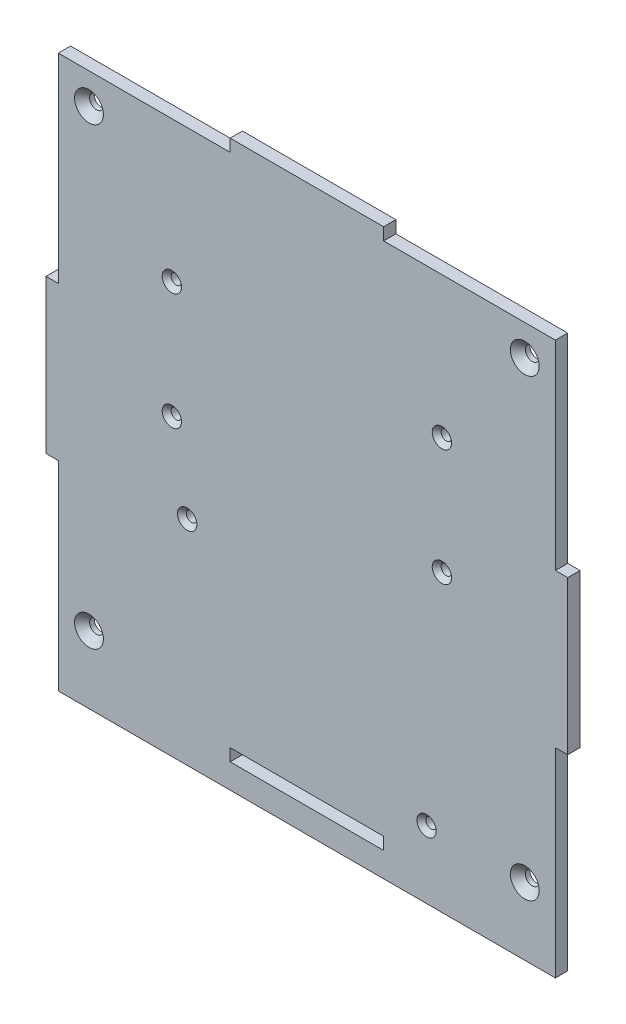
SolidWorks part; units mm, degrees
ref_plane "Front Plane" through (0, 0, 0) normal (0, 0, 1) x (1, 0, 0)
ref_plane "Top Plane" through (0, 0, 0) normal (0, 1, 0) x (1, 0, 0)
ref_plane "Right Plane" through (0, 0, 0) normal (1, 0, 0) x (0, 0, -1)
sketch "Sketch1" plane through (0, 0, 0) normal (0, 0, 1) x (1, 0, 0)
  line L0 (0, 104) -> (0, 10) construction
  line L1 (-81, -80) -> (81, -80)
  line L2 (-81, -80) -> (-81, 100)
  line L3 (-81, 100) -> (81, 100)
  line L4 (81, -80) -> (81, 100)
  line L5 (-81, -80) -> (81, 100) construction
  line L6 (-81, 100) -> (81, -80) construction
  line L7 (-81, 35) -> (-85, 35)
  line L8 (-81, 35) -> (-81, -15)
  line L9 (-81, -15) -> (-85, -15)
  line L10 (-85, 35) -> (-85, -15)
  line L11 (-25, 100) -> (25, 100)
  line L12 (-25, 100) -> (-25, 104)
  line L13 (-25, 104) -> (25, 104)
  line L14 (25, 100) -> (25, 104)
  line L15 (0, 10) -> (-85, 10) construction
  line L24 (81, -15) -> (85, -15)
  line L25 (85, 35) -> (85, -15)
  line L26 (81, 35) -> (85, 35)
  line L27 (81, 35) -> (81, -15)
  line L28 (0, 10) -> (0, 0)
  point P0 (0, 0)
  dimension "D1" = 162
  dimension "D2" = 180
  dimension "D3" = 4
  dimension "D4" = 4
  dimension "D5" = 50
  dimension "D6" = 50
  dimension "D7" = 100
extrude "Boss-Extrude2" add sketch "Sketch1" along normal blind 4
sketch "Sketch2" plane through (0, 0, 4) normal (0, 0, 1) x (1, 0, 0)
  line L0 (0, 0) -> (0, -70)
  line L1 (-25, -72) -> (25, -72)
  line L2 (-25, -72) -> (-25, -68)
  line L3 (-25, -68) -> (25, -68)
  line L4 (25, -72) -> (25, -68)
  line L5 (-25, -72) -> (25, -68) construction
  line L6 (-25, -68) -> (25, -72) construction
  point P0 (0, -70)
  dimension "D1" = 70
  dimension "D2" = 50
  dimension "D3" = 4
extrude "Cut-Extrude1" cut sketch "Sketch2" against normal up to next contours L3 L4 L1 L2
sketch "Sketch3" plane through (0, 0, 4) normal (0, 0, 1) x (1, 0, 0)
  line L0 (0, 35) -> (0, 0)
  line L1 (-44, 16) -> (44, 16)
  line L2 (-44, 16) -> (-44, 54)
  line L3 (-44, 54) -> (44, 54)
  line L4 (44, 16) -> (44, 54)
  line L5 (-44, 16) -> (44, 54) construction
  line L6 (-44, 54) -> (44, 16) construction
  point P0 (0, 35)
  dimension "D1" = 88
  dimension "D2" = 38
  dimension "D3" = 35
hole_wizard "CSK for M3 Countersunk Flat Head Screw1" positions "3DSketch1" profile "Sketch4" countersink size "M3" standard "ISO" end condition up to next
sketch3d "3DSketch1"
  point P0 (-44, 54, 4)
  point P3 (44, 54, 4)
  point P6 (44, 16, 4)
  point P9 (-44, 16, 4)
sketch "Sketch4" plane through (-44, 54, 4) normal (1, 0, 0) x (0, -1, 0)
  line L0 (0, 0) -> (0, 4)
  line L1 (0, 4) -> (1.7, 4)
  line L2 (1.7, 4) -> (1.7, 1.45)
  line L3 (1.7, 1.45) -> (3.15, 0)
  line L5 (3.15, 0) -> (0, 0)
  line L6 (-1.7, 1.45) -> (-3.15, 0) construction
  line L11 (0, -6.35) -> (0, 107.95) construction
  dimension "Thru Hole Dia." = 3.4
  dimension "Thru Hole Depth" = 4
  dimension "Near C'Sink Dia." = 6.3
  dimension "Near C'Sink Angle" = 90
sketch "Sketch5" plane through (0, 0, 4) normal (0, 0, 1) x (1, 0, 0)
  line L0 (-25, -68) -> (25, -68) construction
  line L1 (-71, 90) -> (71, 90)
  line L2 (-71, 90) -> (-71, -58)
  line L3 (-71, -58) -> (71, -58)
  line L4 (71, 90) -> (71, -58)
  line L5 (25, 100) -> (81, 100) construction
  line L6 (81, 35) -> (81, 100) construction
  line L7 (-81, 35) -> (-81, 100) construction
  dimension "D1" = 10
  dimension "D2" = 10
  dimension "D3" = 10
  dimension "D4" = 10
hole_wizard "CSK for M4 Countersunk Flat Head Screw1" positions "3DSketch2" profile "Sketch6" countersink size "M4" standard "ISO" end condition up to next
sketch3d "3DSketch2"
  point P0 (-71, 90, 4)
  point P3 (71, 90, 4)
  point P6 (71, -58, 4)
  point P9 (-71, -58, 4)
sketch "Sketch6" plane through (-71, 90, 4) normal (1, 0, 0) x (0, -1, 0)
  line L0 (0, 0) -> (0, 4)
  line L1 (0, 4) -> (2.25, 4)
  line L2 (2.25, 4) -> (2.25, 2.45)
  line L3 (2.25, 2.45) -> (4.7, 0)
  line L5 (4.7, 0) -> (0, 0)
  line L6 (-2.25, 2.45) -> (-4.7, 0) construction
  line L11 (0, -6.35) -> (0, 107.95) construction
  dimension "Thru Hole Dia." = 4.5
  dimension "Thru Hole Depth" = 4
  dimension "Near C'Sink Dia." = 9.4
  dimension "Near C'Sink Angle" = 90
sketch "Sketch7" plane through (0, 0, 4) normal (0, 0, 1) x (1, 0, 0)
  line L0 (-25, -68) -> (25, -68) construction
  line L5 (-39, -58) -> (39, -58)
  line L6 (-39, -58) -> (-39, -10.5)
  line L7 (-39, -10.5) -> (39, -10.5)
  line L8 (39, -58) -> (39, -10.5)
  line L9 (-39, -58) -> (39, -10.5) construction
  line L10 (-39, -10.5) -> (39, -58) construction
  line L11 (0, 0) -> (0, -34.25)
  point P0 (0, -34.25)
  dimension "D1" = 47.5
  dimension "D2" = 78
  dimension "D3" = 10
hole_wizard "CSK for M3 Countersunk Flat Head Screw3" positions "3DSketch4" profile "Sketch9" countersink size "M3" standard "ISO" end condition up to next
sketch3d "3DSketch4"
  point P0 (-39, -10.5, 4)
  point P3 (39, -58, 4)
sketch "Sketch9" plane through (-39, -10.5, 4) normal (1, 0, 0) x (0, -1, 0)
  line L0 (0, 0) -> (0, 4)
  line L1 (0, 4) -> (1.7, 4)
  line L2 (1.7, 4) -> (1.7, 1.45)
  line L3 (1.7, 1.45) -> (3.15, 0)
  line L5 (3.15, 0) -> (0, 0)
  line L6 (-1.7, 1.45) -> (-3.15, 0) construction
  line L11 (0, -6.35) -> (0, 107.95) construction
  dimension "Thru Hole Dia." = 3.4
  dimension "Thru Hole Depth" = 4
  dimension "Near C'Sink Dia." = 6.3
  dimension "Near C'Sink Angle" = 90
